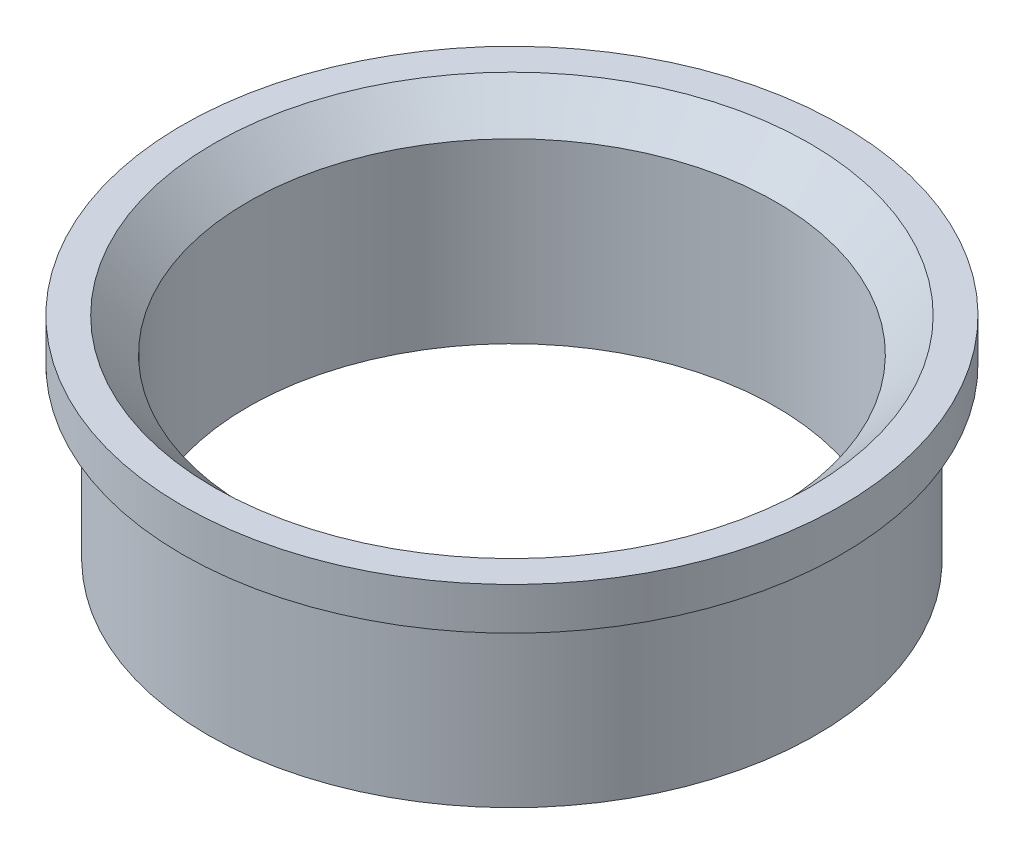
SolidWorks part; units mm, degrees
ref_plane "Front Plane" through (0, 0, 0) normal (0, 0, 1) x (1, 0, 0)
ref_plane "Top Plane" through (0, 0, 0) normal (0, 1, 0) x (1, 0, 0)
ref_plane "Right Plane" through (0, 0, 0) normal (1, 0, 0) x (0, 0, -1)
sketch "Sketch1" plane through (0, 0, 0) normal (0, 0, 1) x (1, 0, 0)
  line L0 (0, 43.1755) -> (0, -40.6357) construction
  line L1 (-51.9234, 0) -> (61.2358, 0) construction
  line L2 (62.5, 0) -> (62.5, 42)
  line L3 (62.5, 42) -> (70.5, 50)
  line L4 (70.5, 50) -> (78, 50)
  line L5 (78, 50) -> (78, 40)
  line L6 (78, 40) -> (72, 40)
  line L7 (72, 40) -> (72, 0)
  line L8 (72, 0) -> (62.5, 0)
  point P7 (31.5495, 19.855)
  point P13 (18.5551, 33.1486)
  point P14 (30.9117, 34.8887)
  point P15 (19.7092, 9.5536)
  dimension "D1" = 135
  dimension "D2" = 8
  dimension "D3" = 10
  dimension "D4" = 40
  dimension "D5" = 62.5
  dimension "D6" = 72
  dimension "D7" = 78
revolve "Revolve1" add sketch "Sketch1" angle 360 about L0
